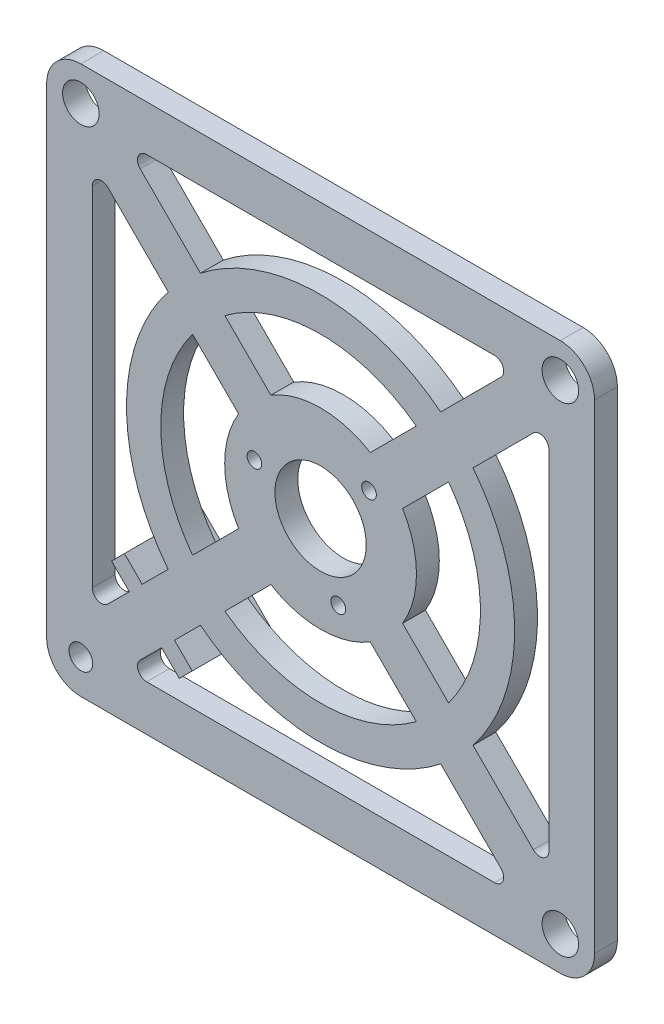
SolidWorks part; units mm, degrees
ref_plane "정면" through (0, 0, 0) normal (0, 0, 1) x (1, 0, 0)
ref_plane "윗면" through (0, 0, 0) normal (0, 1, 0) x (1, 0, 0)
ref_plane "우측면" through (0, 0, 0) normal (1, 0, 0) x (0, 0, -1)
sketch "Sketch1" plane through (0, 0, 0) normal (0, 0, 1) x (1, 0, 0)
  line L0 (-50, 50) -> (-50, -50)
  line L1 (-52.5, 60) -> (52.5, 60)
  line L2 (-60, 52.5) -> (-60, -52.5)
  line L3 (-52.5, -60) -> (52.5, -60)
  line L4 (60, 52.5) -> (60, -52.5)
  line L5 (-50, -50) -> (50, -50)
  line L6 (50, 50) -> (50, -50)
  line L7 (-50, 50) -> (50, 50)
  line L8 (-50, 42.9289) -> (-17.9577, 10.8867)
  line L9 (-42.9289, 50) -> (-10.8867, 17.9577)
  line L10 (-50, 50) -> (50, -50) construction
  line L11 (-50, -50) -> (50, 50) construction
  line L12 (50, 42.9289) -> (17.9577, 10.8867)
  line L13 (42.9289, 50) -> (10.8867, 17.9577)
  line L14 (42.9289, -50) -> (10.8867, -17.9577)
  line L15 (50, -42.9289) -> (17.9577, -10.8867)
  line L16 (-50, -42.9289) -> (-17.9577, -10.8867)
  line L17 (-42.9289, -50) -> (-10.8867, -17.9577)
  arc A0 (52.5, 60) -> (60, 52.5) centre (52.5, 52.5) cw
  arc A1 (52.5, -60) -> (60, -52.5) centre (52.5, -52.5) ccw
  arc A2 (-60, -52.5) -> (-52.5, -60) centre (-52.5, -52.5) ccw
  arc A3 (-52.5, 60) -> (-60, 52.5) centre (-52.5, 52.5) ccw
  arc A4 (-50, -50) -> (-50, -50) centre (-50, -50) ccw
  arc A5 (50, -50) -> (50, -50) centre (50, -50) ccw
  arc A6 (50, 50) -> (50, 50) centre (50, 50) cw
  arc A7 (-50, 50) -> (-50, 50) centre (-50, 50) ccw
  circle A8 centre (0, 0) radius 21
  circle A9 centre (0, 0) radius 35
  circle A10 centre (0, 0) radius 42.5
  circle A11 centre (-52.5, -52.5) radius 4
  circle A12 centre (-52.5, 52.5) radius 4
  circle A13 centre (52.5, 52.5) radius 4
  circle A14 centre (52.5, -52.5) radius 4
  circle A15 centre (0, 0) radius 10
  point P4 (60, 0)
  point P6 (0, 60)
  point P9 (60, 60)
  point P14 (-60, -60)
  point P17 (-60, 60)
  point P51 (0, 0)
  point P61 (0, 0)
  dimension "D3" = 7.5
  dimension "D5" = 42
  dimension "D9" = 70
  dimension "D10" = 85
  dimension "D11" = 8
  dimension "D12" = 4
  dimension "D13" = 105
  dimension "D14" = 7.5
  dimension "D15" = 20
  dimension "D1" = 120
  dimension "D2" = 120
  dimension "D6" = 10
  dimension "D7" = 5
  dimension "D4" = 10
  dimension "D8" = 4
extrude "Extrude1" add sketch "Sketch1" along normal mid plane 5 contours A8 | L13 A10 L9 A9 | L9 A10 L8 A9 | L8 A10 L16 A9 | L16 A10 L17 A9 | L17 A10 L14 A9 | L15 A10 L12 A9 | L16 A9 L17 A8 | L12 A9 L13 A8 | L14 A9 L15 A8 | L9 A9 L8 A8 | L12 A10 L13 A9 | L14 A10 L15 A9 | A10 L14 L5 L6 L15 | A10 L16 L0 L5 L17 | A10 L12 L6 L7 L13 | A10 L9 L7 L0 L8 | L1 A3 L2 A2 L3 A1 L4 A0 L0 L7 L6 L5
fillet "Fillet1" radius 2 8 edges at (-50, -42.9289, 0) (-42.9289, -50, 0) (50, -42.9289, 0) (42.9289, -50, 0) (50, 42.9289, 0) (42.9289, 50, 0) (-42.9289, 50, 0) (-50, 42.9289, 0)
sketch "Sketch6" plane through (0, 0, -2.5) normal (0, 0, -1) x (-1, 0, 0)
  line L0 (0, 0) -> (-52.5, 52.5) construction
  circle A0 centre (0, 0) radius 15 construction
  circle A1 centre (-10.6066, 10.6066) radius 1.6
  circle A2 centre (14.4889, 3.8823) radius 1.6
  circle A3 centre (-3.8823, -14.4889) radius 1.6
  point P14 (0, 0)
  dimension "D1" = 30
  dimension "D2" = 3.2
  dimension "D3" = 3
extrude "Extrude5" cut sketch "Sketch6" against normal up to next
sketch "Sketch7" plane through (0, 0, 2.5) normal (0, 0, 1) x (1, 0, 0)
  circle A0 centre (-52.5, -52.5) radius 4
  circle A1 centre (-52.5, -52.5) radius 4 construction
extrude "Extrude6" add sketch "Sketch7" against normal up to surface (5 mm away)
sketch "Sketch10" plane through (0, 0, -2.5) normal (0, 0, -1) x (-1, 0, 0)
  circle A0 centre (52.5, -52.5) radius 2.6
  dimension "D1" = 5.2
extrude "Extrude7" cut sketch "Sketch10" against normal blind 10
sketch "Sketch11" plane through (0, 0, -2.5) normal (0, 0, -1) x (-1, 0, 0)
  line L0 (28.1048, -42.9541) -> (42.9541, -28.1048)
  line L1 (42.9541, -28.1048) -> (45.7825, -30.9332)
  line L2 (45.7825, -30.9332) -> (30.9332, -45.7825)
  line L3 (30.9332, -45.7825) -> (28.1048, -42.9541)
  line L4 (0, 0) -> (57.8033, -57.8033) construction
  line L5 (39.5147, -46.5858) -> (26.3078, -33.3789) construction
  arc A0 (52.5, -60) -> (60, -52.5) centre (52.5, -52.5) ccw construction
  circle A1 centre (52.5, -52.5) radius 2.6 construction
  point P10 (35.5294, -35.5294)
  point P13 (28.0499, -42.1786)
  dimension "D3" = 20
  dimension "D1" = 21
  dimension "D2" = 4
  dimension "D4" = 90
extrude "Extrude8" add sketch "Sketch11" along normal blind 12 and the other way up to surface other way up to face at (-49.9, -52.5, 2.5)
sketch "Sketch12" plane through (-35.5294, -35.5294, 0) normal (0.7071, 0.7071, 0) x (0, 0, -1)
  line L0 (5, 8.25) -> (5, -8.25) construction
  line L1 (2.5, -5) -> (2.5, 5) construction
  line L2 (14.5, 10.5) -> (14.5, -10.5) construction
  circle A0 centre (5, -8.25) radius 1.3
  circle A1 centre (5, 8.25) radius 1.3
  point P5 (0, 0)
  point P8 (14.5, 0)
  dimension "D1" = 2.6
  dimension "D2" = 2.6
  dimension "D3" = 16.5
  dimension "D4" = 2.5
  dimension "D5" = 8.25
extrude "Extrude9" cut sketch "Sketch12" against normal blind 10
